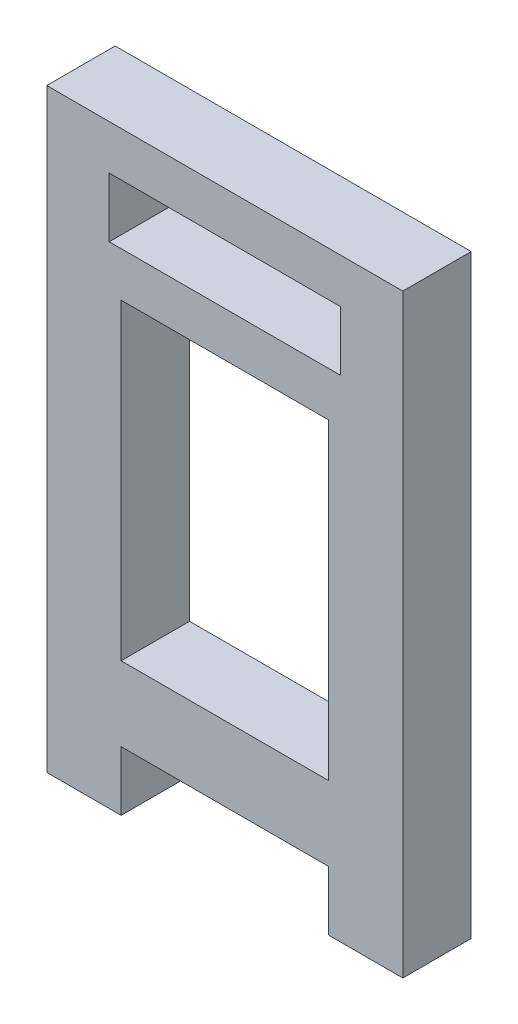
SolidWorks part; units mm, degrees
ref_plane "Front Plane" through (0, 0, 0) normal (0, 0, 1) x (1, 0, 0)
ref_plane "Top Plane" through (0, 0, 0) normal (0, 1, 0) x (1, 0, 0)
ref_plane "Right Plane" through (0, 0, 0) normal (1, 0, 0) x (0, 0, -1)
sketch "Sketch1" plane through (0, 0, 0) normal (0, 0, 1) x (1, 0, 0)
  line L0 (0, 0) -> (0, -2)
  line L1 (2.5, 0) -> (9.47, 0)
  line L2 (0, 0) -> (0, 18)
  line L3 (0, 18) -> (11.97, 18)
  line L4 (11.97, 0) -> (11.97, 18)
  line L5 (0, -2) -> (2.5, -2)
  line L6 (2.5, -2) -> (2.5, 0)
  line L7 (11.97, 0) -> (11.97, -2)
  line L8 (11.97, -2) -> (9.47, -2)
  line L9 (9.47, -2) -> (9.47, 0)
  line L12 (2.5, 2.5) -> (9.47, 2.5)
  line L13 (2.5, 2.5) -> (2.5, 13)
  line L14 (2.5, 13) -> (9.47, 13)
  line L15 (9.47, 2.5) -> (9.47, 13)
  line L16 (2.1, 14.5) -> (9.87, 14.5)
  line L17 (2.1, 14.5) -> (2.1, 16.5)
  line L18 (2.1, 16.5) -> (9.87, 16.5)
  line L19 (9.87, 14.5) -> (9.87, 16.5)
  dimension "D1" = 18
  dimension "D2" = 2.5
  dimension "D3" = 6.97
  dimension "D4" = 2
  dimension "D5" = 2
  dimension "D6" = 2.5
  dimension "D7" = 2.5
  dimension "D8" = 10.5
  dimension "D9" = 2
  dimension "D10" = 1.5
  dimension "D12" = 0.4
extrude "Boss-Extrude1" add sketch "Sketch1" along normal blind 2.3
